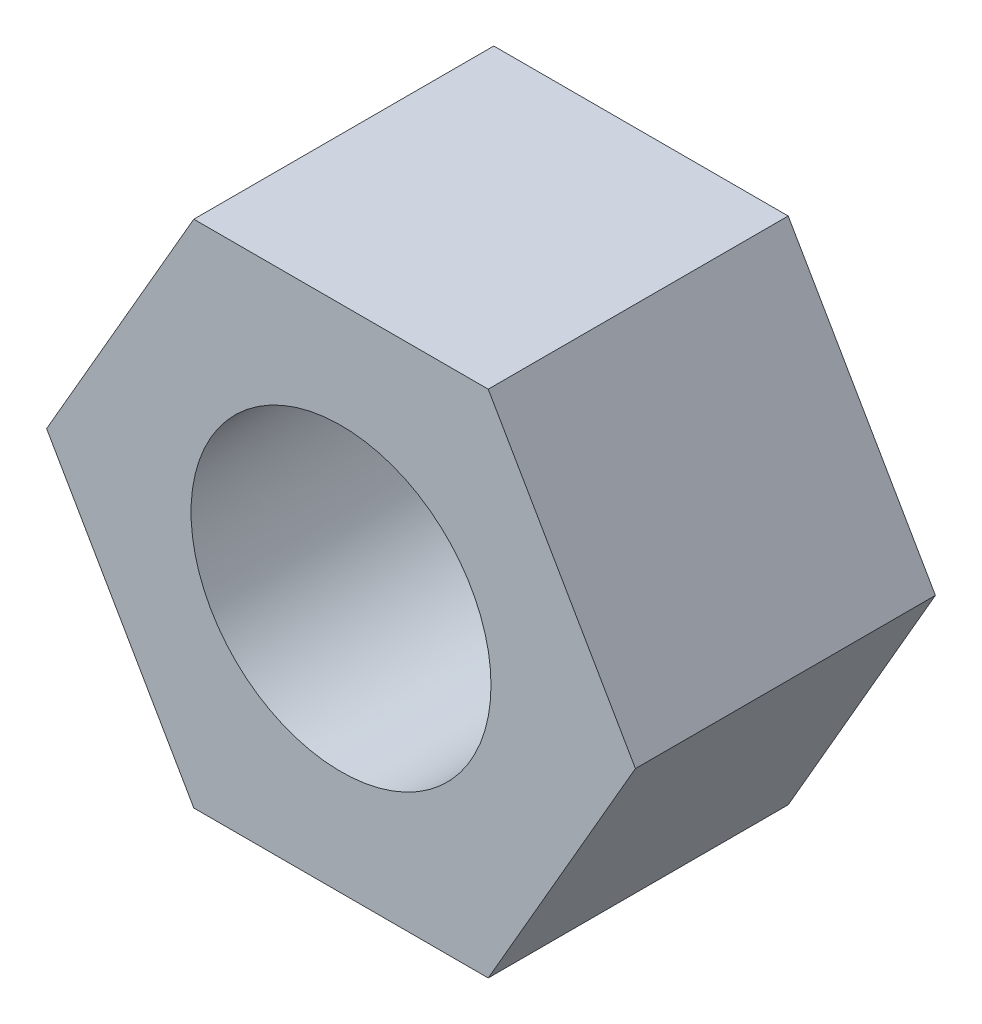
SolidWorks part; units mm, degrees
ref_plane "Front Plane" through (0, 0, 0) normal (0, 0, 1) x (1, 0, 0)
ref_plane "Top Plane" through (0, 0, 0) normal (0, 1, 0) x (1, 0, 0)
ref_plane "Right Plane" through (0, 0, 0) normal (1, 0, 0) x (0, 0, -1)
sketch "Sketch1" plane through (0, 0, 0) normal (0, 0, 1) x (1, 0, 0)
  line L1 (4.9075, 8.5) -> (-4.9075, 8.5)
  line L2 (-4.9075, 8.5) -> (-9.815, 0)
  line L3 (-9.815, 0) -> (-4.9075, -8.5)
  line L4 (-4.9075, -8.5) -> (4.9075, -8.5)
  line L5 (4.9075, -8.5) -> (9.815, 0)
  line L6 (9.815, 0) -> (4.9075, 8.5)
  circle A0 centre (0, 0) radius 8.5 construction
  dimension "D1" = 17
extrude "Boss-Extrude1" add sketch "Sketch1" along normal blind 10
sketch "Sketch2" plane through (0, 0, 10) normal (0, 0, 1) x (1, 0, 0)
  circle A0 centre (0, 0) radius 5
  dimension "D1" = 10
extrude "Cut-Extrude1" cut sketch "Sketch2" against normal blind 10
